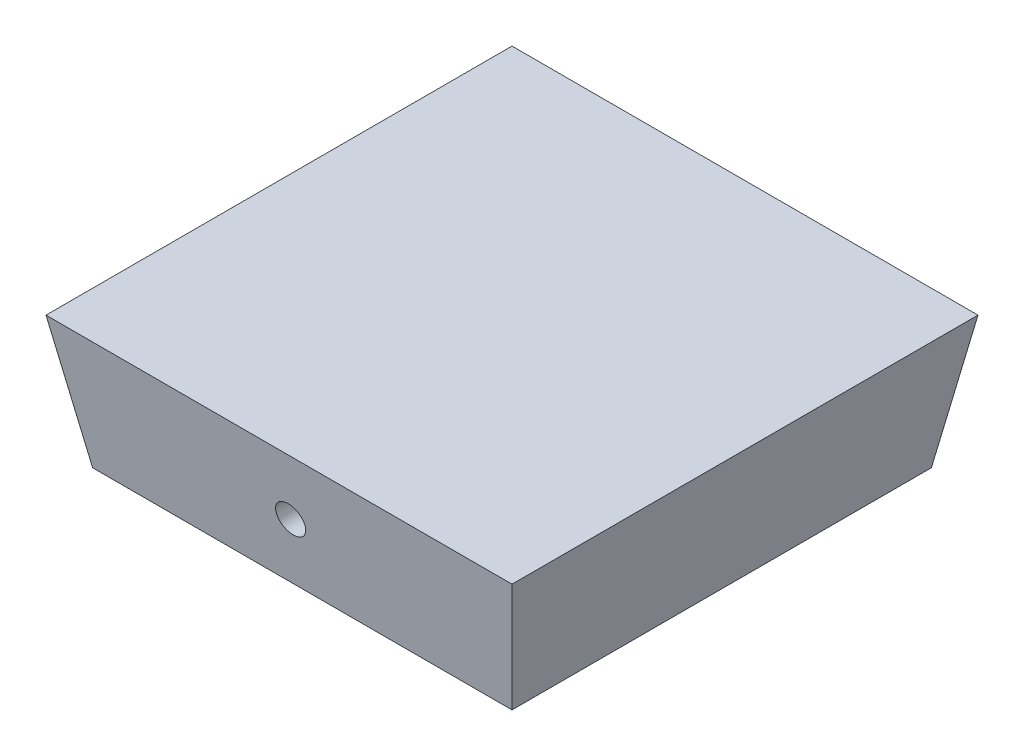
SolidWorks part; units mm, degrees
ref_plane "Plan de face" through (0, 0, 0) normal (0, 0, 1) x (1, 0, 0)
ref_plane "Plan de dessus" through (0, 0, 0) normal (0, 1, 0) x (1, 0, 0)
ref_plane "Plan de droite" through (0, 0, 0) normal (1, 0, 0) x (0, 0, -1)
sketch "Esquisse1" plane through (0, 0, 0) normal (0, 1, 0) x (1, 0, 0)
  line L1 (-23.495, -23.495) -> (23.495, -23.495)
  line L2 (-23.495, -23.495) -> (-23.495, 23.495)
  line L3 (-23.495, 23.495) -> (23.495, 23.495)
  line L4 (23.495, -23.495) -> (23.495, 23.495)
  line L5 (-23.495, -23.495) -> (23.495, 23.495) construction
  line L6 (-23.495, 23.495) -> (23.495, -23.495) construction
  point P0 (0, 0)
  dimension "D1" = 46.99
  dimension "D2" = 46.99
extrude "Boss.-Extru.1" add sketch "Esquisse1" along normal blind 14.8158 draft 10 draft outward yes
ref_plane "Plan1" through (0, 0, 26.67) normal (0, 0, 1) x (1, 0, 0)
sketch "Esquisse4" plane through (0, 0, 26.67) normal (0, 0, 1) x (1, 0, 0)
  line L0 (-23.495, 0) -> (0, 0)
  line L1 (0, 0) -> (0, 7.4079)
  circle A0 centre (0, 7.4079) radius 1.6669
  dimension "D1" = 3.3337
extrude "Enlèv. mat.-Extru.1" cut sketch "Esquisse4" against normal blind 12.7 contours A0
